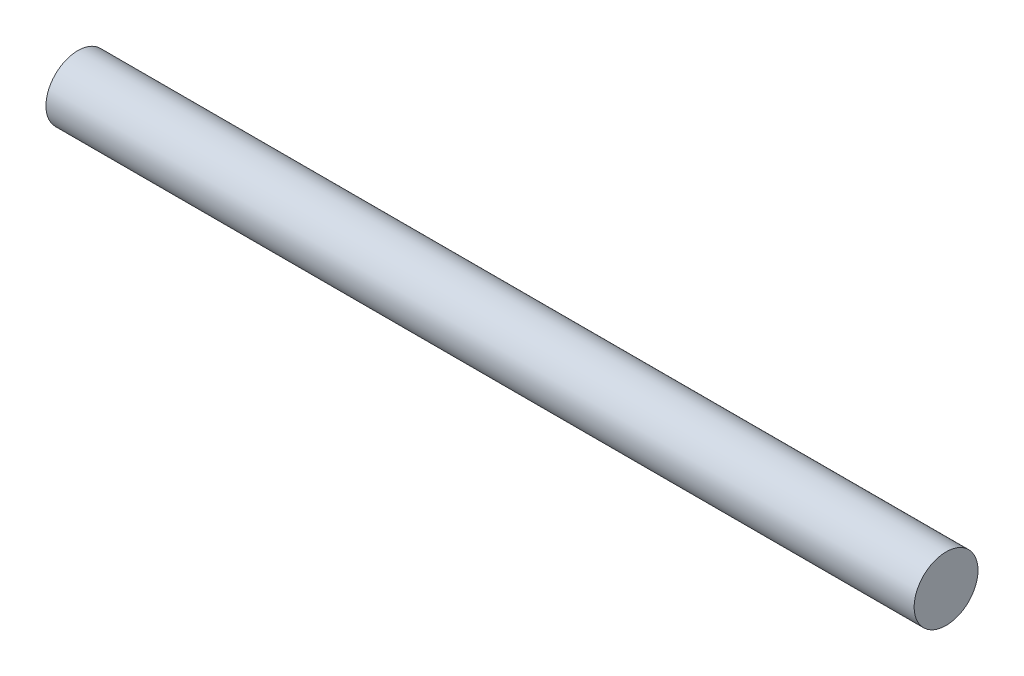
SolidWorks part; units mm, degrees
material "Cast Alloy Steel"
ref_plane "Front Plane" through (0, 0, 0) normal (0, 0, 1) x (1, 0, 0)
ref_plane "Top Plane" through (0, 0, 0) normal (0, 1, 0) x (1, 0, 0)
ref_plane "Right Plane" through (0, 0, 0) normal (1, 0, 0) x (0, 0, -1)
sketch "Sketch1" plane through (0, 0, 0) normal (1, 0, 0) x (0, 0, -1)
  circle A0 centre (0, 0) radius 1.25
  dimension "D1" = 2.5
extrude "Boss-Extrude1" add sketch "Sketch1" along normal blind 34
